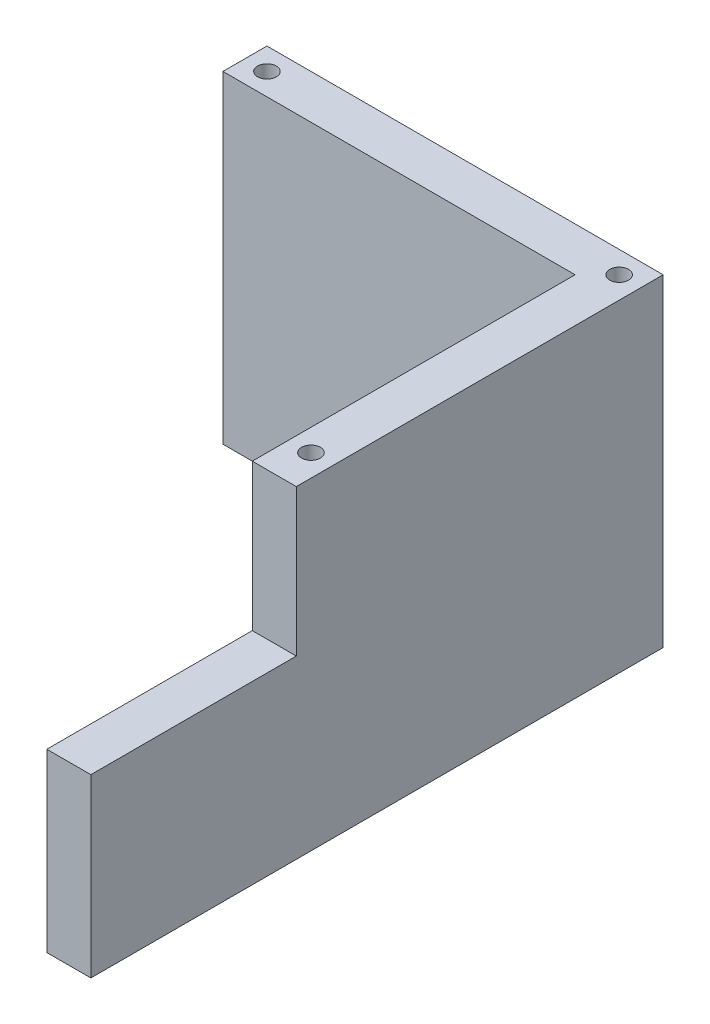
SolidWorks part; units mm, degrees
material "ABS"
ref_plane "Front Plane" through (0, 0, 0) normal (0, 0, 1) x (1, 0, 0)
ref_plane "Top Plane" through (0, 0, 0) normal (0, 1, 0) x (1, 0, 0)
ref_plane "Right Plane" through (0, 0, 0) normal (1, 0, 0) x (0, 0, -1)
sketch "Sketch1" plane through (0, 0, 0) normal (0, 1, 0) x (1, 0, 0)
  line L5 (0, -123.825) -> (0, 0)
  line L6 (0, 0) -> (-85.725, 0)
  line L7 (-85.725, 0) -> (-85.725, -9.525)
  line L8 (-85.725, -9.525) -> (-9.525, -9.525)
  line L9 (-9.525, -9.525) -> (-9.525, -123.825)
  line L10 (-9.525, -123.825) -> (0, -123.825)
  dimension "D1" = 9.525
  dimension "D2" = 9.525
  dimension "D3" = 114.3
  dimension "D4" = 76.2
extrude "Boss-Extrude1" add sketch "Sketch1" along normal blind 69.85
hole_wizard "CBORE for #4 Socket Head Cap Screw1" positions "Sketch3" profile "Sketch2" counterbore size "#4" standard "ANSI Inch"
sketch "Sketch3" plane through (0, 0, 0) normal (0, -1, 0) x (-1, 0, 0)
  line L6 (0, -123.825) -> (0, 0) construction
  line L8 (0, -4.7625) -> (85.725, -4.7625) construction
  line L9 (85.725, 0) -> (85.725, -9.525) construction
  line L11 (4.7625, -123.825) -> (4.7625, 0) construction
  line L12 (9.525, -123.825) -> (0, -123.825) construction
  line L13 (0, 0) -> (85.725, 0) construction
  point P47 (4.7625, -4.7625)
  point P54 (4.7625, -74.6125)
  point P60 (4.7625, -109.5375)
  point P66 (4.7625, -39.6875)
  point P74 (74.6125, -4.7625)
  point P77 (39.6875, -4.7625)
  dimension "D1" = 34.925
  dimension "D2" = 34.925
  dimension "D3" = 34.925
  dimension "D6" = 34.925
  dimension "D7" = 34.925
sketch "Sketch2" plane through (-4.7625, 0, 4.7625) normal (1, 0, 0) x (0, 0, -1)
  line L0 (0, 0) -> (0, 10.5056)
  line L1 (0, 10.5056) -> (1.6319, 9.525)
  line L2 (1.6319, 9.525) -> (1.6319, 4.7625)
  line L3 (1.6319, 4.7625) -> (1.9844, 4.7625)
  line L4 (1.9844, 4.7625) -> (1.9844, 0)
  line L5 (1.9844, 0) -> (0, 0)
  line L10 (0, 10.5056) -> (-1.632, 9.525) construction
  line L11 (0, -6.35) -> (0, 107.95) construction
  dimension "Hole Dia." = 3.2639
  dimension "Hole Depth" = 9.525
  dimension "C'Bore Dia." = 3.9688
  dimension "C'Bore Depth" = 4.7625
  dimension "Drill Angle" = 118
sketch "Sketch4" plane through (0, 69.85, 0) normal (0, 1, 0) x (1, 0, 0)
  line L2 (-85.725, -4.7625) -> (0, -4.7625) construction
  line L3 (-85.725, 0) -> (-85.725, -9.525) construction
  line L4 (0, -123.825) -> (0, 0) construction
  line L5 (-4.7625, -123.825) -> (-4.7625, 0) construction
  line L6 (-9.525, -123.825) -> (0, -123.825) construction
  line L7 (0, 0) -> (-85.725, 0) construction
  circle A0 centre (-4.7625, -4.7625) radius 2.032
  circle A1 centre (-4.7625, -71.4375) radius 2.032
  circle A2 centre (-80.9625, -4.7625) radius 2.032
  dimension "D1" = 4.064
  dimension "D2" = 4.064
  dimension "D3" = 4.064
  dimension "D4" = 76.2
  dimension "D5" = 66.675
extrude "Cut-Extrude1" cut sketch "Sketch4" against normal blind 4.7625
sketch "Sketch6" plane through (0, 0, 0) normal (1, 0, 0) x (0, 0, -1)
  line L7 (-123.825, 69.85) -> (-79.375, 69.85)
  line L8 (-123.825, 69.85) -> (-123.825, 38.1)
  line L9 (-123.825, 38.1) -> (-79.375, 38.1)
  line L10 (-79.375, 69.85) -> (-79.375, 38.1)
  line L11 (-123.825, 69.85) -> (-79.375, 38.1) construction
  line L12 (-123.825, 38.1) -> (-79.375, 69.85) construction
  point P10 (-101.6, 53.975)
  dimension "D3" = 31.75
  dimension "D4" = 44.45
sketch "Sketch7" plane through (0, 65.0875, 0) normal (0, 1, 0) x (1, 0, 0)
  circle A0 centre (-80.9625, -4.7625) radius 1.632
  circle A1 centre (-4.7625, -4.7625) radius 1.632
  circle A2 centre (-4.7625, -71.4375) radius 1.6319
  dimension "D1" = 3.2639
  dimension "D2" = 3.2639
  dimension "D3" = 3.2639
extrude "Cut-Extrude4" cut sketch "Sketch7" against normal blind 3.175
extrude "Cut-Extrude3" cut sketch "Sketch6" against normal up to next
